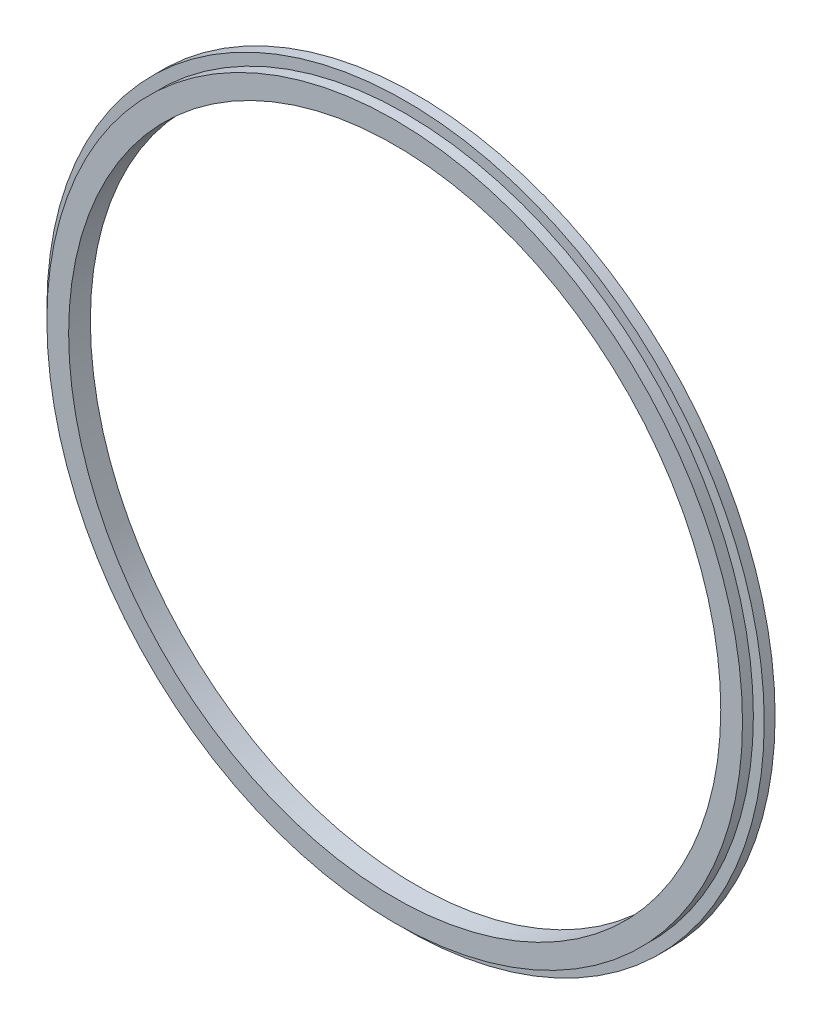
SolidWorks part; units mm, degrees
ref_plane "Front Plane" through (0, 0, 0) normal (0, 0, 1) x (1, 0, 0)
ref_plane "Top Plane" through (0, 0, 0) normal (0, 1, 0) x (1, 0, 0)
ref_plane "Right Plane" through (0, 0, 0) normal (1, 0, 0) x (0, 0, -1)
sketch "Sketch1" plane through (0, 0, 0) normal (0, 0, 1) x (1, 0, 0)
  circle A0 centre (0, 0) radius 64
  circle A1 centre (0, 0) radius 60
  dimension "D1" = 128
  dimension "D2" = 4
extrude "Boss-Extrude1" add sketch "Sketch1" along normal blind 2
sketch "Sketch3" plane through (0, 0, 0) normal (0, 0, -1) x (-1, 0, 0)
  circle A0 centre (0, 0) radius 60 construction
  circle A1 centre (0, 0) radius 60
  circle A2 centre (0, 0) radius 66
  circle A3 centre (0, 0) radius 64 construction
  dimension "D1" = 2
extrude "Boss-Extrude2" add sketch "Sketch3" along normal blind 2
